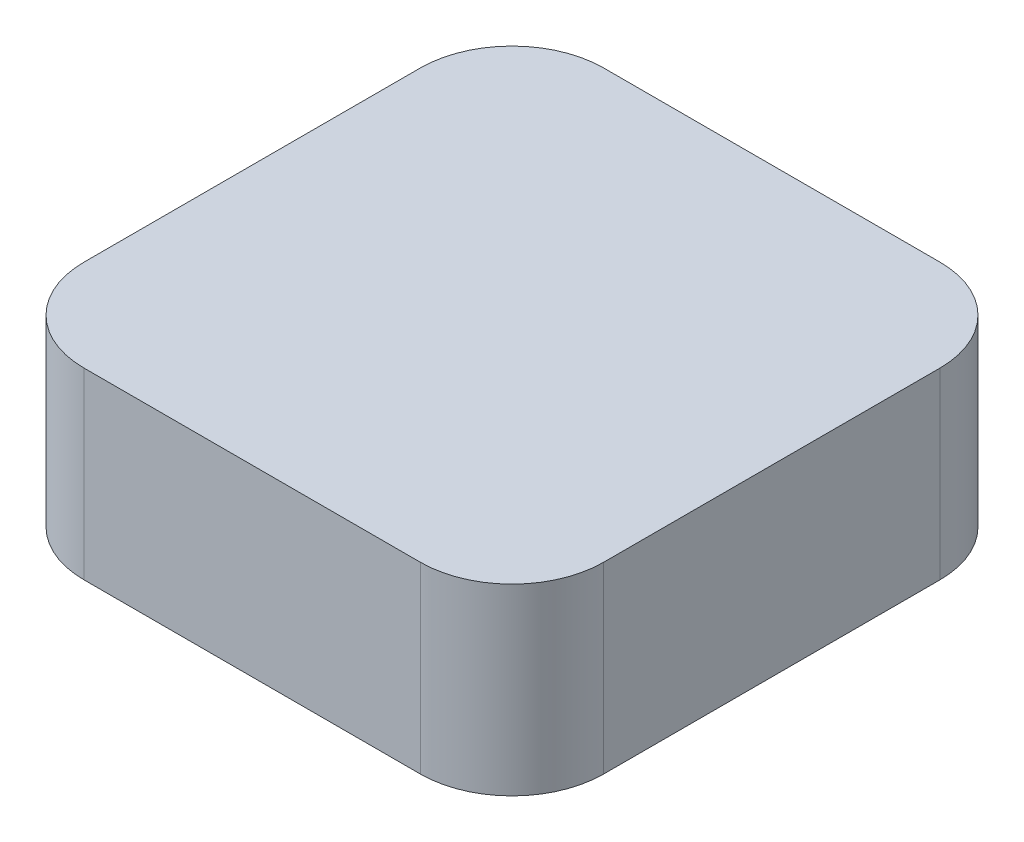
SolidWorks part; units mm, degrees
ref_plane "Front Plane" through (0, 0, 0) normal (0, 0, 1) x (1, 0, 0)
ref_plane "Top Plane" through (0, 0, 0) normal (0, 1, 0) x (1, 0, 0)
ref_plane "Right Plane" through (0, 0, 0) normal (1, 0, 0) x (0, 0, -1)
sketch "Sketch1" plane through (0, 0, 0) normal (0, 1, 0) x (1, 0, 0)
  line L0 (-5.5, 90) -> (5.5, 90)
  line L1 (8.5, 87) -> (8.5, 76)
  line L2 (5.5, 73) -> (-5.5, 73)
  line L3 (-8.5, 76) -> (-8.5, 87)
  arc A0 (-8.5, 87) -> (-5.5, 90) centre (-5.5, 87) cw
  arc A1 (5.5, 90) -> (8.5, 87) centre (5.5, 87) cw
  arc A2 (8.5, 76) -> (5.5, 73) centre (5.5, 76) cw
  arc A3 (-5.5, 73) -> (-8.5, 76) centre (-5.5, 76) cw
extrude "Cap" add sketch "Sketch1" along normal blind 6 from offset 74
sketch "Sketch2" plane through (0, 0, 0) normal (0, 1, 0) x (1, 0, 0)
  line L0 (-3.3, 85.2) -> (3.3, 85.2)
  line L1 (3.7, 84.8) -> (3.7, 78.2)
  line L2 (3.3, 77.8) -> (-3.3, 77.8)
  line L3 (-3.7, 78.2) -> (-3.7, 84.8)
  arc A0 (-3.7, 84.8) -> (-3.3, 85.2) centre (-3.3, 84.8) cw
  arc A1 (3.3, 85.2) -> (3.7, 84.8) centre (3.3, 84.8) cw
  arc A2 (3.7, 78.2) -> (3.3, 77.8) centre (3.3, 78.2) cw
  arc A3 (-3.3, 77.8) -> (-3.7, 78.2) centre (-3.3, 78.2) cw
extrude "Stem socket" cut sketch "Sketch2" along normal blind 3.2 from offset 73.8
